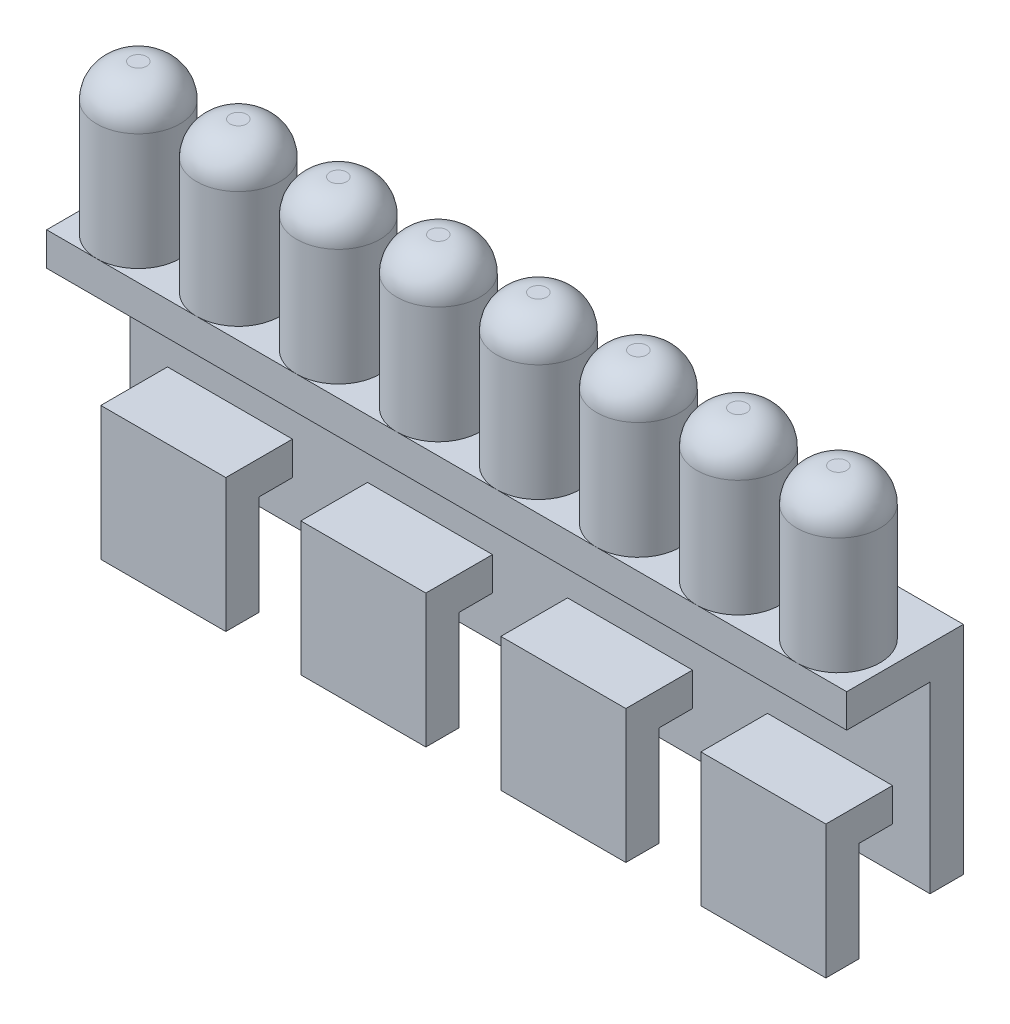
SolidWorks part; units mm, degrees
ref_plane "Plan de face" through (0, 0, 0) normal (0, 0, 1) x (1, 0, 0)
ref_plane "Plan de dessus" through (0, 0, 0) normal (0, 1, 0) x (1, 0, 0)
ref_plane "Plan de droite" through (0, 0, 0) normal (1, 0, 0) x (0, 0, -1)
sketch "Esquisse1" plane through (0, 0, 0) normal (0, 0, 1) x (1, 0, 0)
  line L1 (-6, -6.5) -> (6, -6.5)
  line L2 (-6, -6.5) -> (-6, 6.5)
  line L3 (-6, 6.5) -> (6, 6.5)
  line L4 (6, -6.5) -> (6, 6.5)
  line L5 (-6, -6.5) -> (6, 6.5) construction
  line L6 (-6, 6.5) -> (6, -6.5) construction
  point P0 (0, 0)
  dimension "D1" = 13
  dimension "D2" = 12
extrude "Boss.-Extru.1" add sketch "Esquisse1" along normal blind 2
sketch "Esquisse2" plane through (0, 0, 2) normal (0, 0, 1) x (1, 0, 0)
  line L0 (-6, -6.5) -> (6, -6.5) construction
  line L1 (-3.75, -2) -> (3.75, -2)
  line L2 (-3.75, -2) -> (-3.75, -4)
  line L3 (-3.75, -4) -> (3.75, -4)
  line L4 (3.75, -2) -> (3.75, -4)
  line L5 (0, -6.5) -> (0, 0) construction
  point P9 (0, -4)
  dimension "D1" = 2.5
  dimension "D2" = 2
  dimension "D3" = 7.5
extrude "Boss.-Extru.2" add sketch "Esquisse2" along normal blind 4
sketch "Esquisse3" plane through (0, -4, 0) normal (0, -1, 0) x (1, 0, 0)
  line L0 (3.75, 6) -> (3.75, 2) construction
  line L1 (-3.75, 6) -> (3.75, 6)
  line L2 (-3.75, 6) -> (-3.75, 4)
  line L3 (-3.75, 4) -> (3.75, 4)
  line L4 (3.75, 6) -> (3.75, 4)
  dimension "D1" = 2
extrude "Boss.-Extru.3" add sketch "Esquisse3" along normal blind 6
sketch "Esquisse4" plane through (0, 0, 2) normal (0, 0, 1) x (1, 0, 0)
  line L0 (6, -6.5) -> (6, 6.5) construction
  line L1 (-6, 6.5) -> (6, 6.5)
  line L2 (-6, 6.5) -> (-6, 4.5)
  line L3 (-6, 4.5) -> (6, 4.5)
  line L4 (6, 6.5) -> (6, 4.5)
  dimension "D1" = 2
extrude "Boss.-Extru.4" add sketch "Esquisse4" along normal blind 5
sketch "Esquisse5" plane through (0, 6.5, 0) normal (0, 1, 0) x (1, 0, 0)
  line L0 (0, 0) -> (0, -7) construction
  line L1 (6, -7) -> (-6, -7) construction
  line L3 (-3, -4.5) -> (3, -4.5) construction
  circle A0 centre (-3, -4.5) radius 2.5
  circle A1 centre (3, -4.5) radius 2.5
  point P9 (0, -4.5)
  dimension "D1" = 5
  dimension "D2" = 6
extrude "Boss.-Extru.6" add sketch "Esquisse5" along normal blind 9
fillet "Congé1" radius 2 2 edges at (-3, 15.5, 7) (3, 15.5, 7)
sketch "Esquisse6" plane through (0, 0, 2) normal (0, 0, 1) x (1, 0, 0)
  line L0 (3, 6.5) -> (-3, 6.5) construction
  line L1 (0, -3.85) -> (0, 3.85) construction
  circle A0 centre (0, 1.5) radius 1.25
  point P5 (0, 0)
  point P6 (0, 0)
  dimension "D1" = 2.5
  dimension "D2" = 5
extrude "Enlèv. mat.-Extru.1" cut sketch "Esquisse6" against normal up to next contours A0
pattern_linear "Répétition linéaire1" count 4 spacing 12 along (-1, 0, 0) of "Boss.-Extru.1", "Boss.-Extru.2", "Boss.-Extru.3", "Boss.-Extru.4", "Boss.-Extru.6", "Congé1", "Enlèv. mat.-Extru.1"
